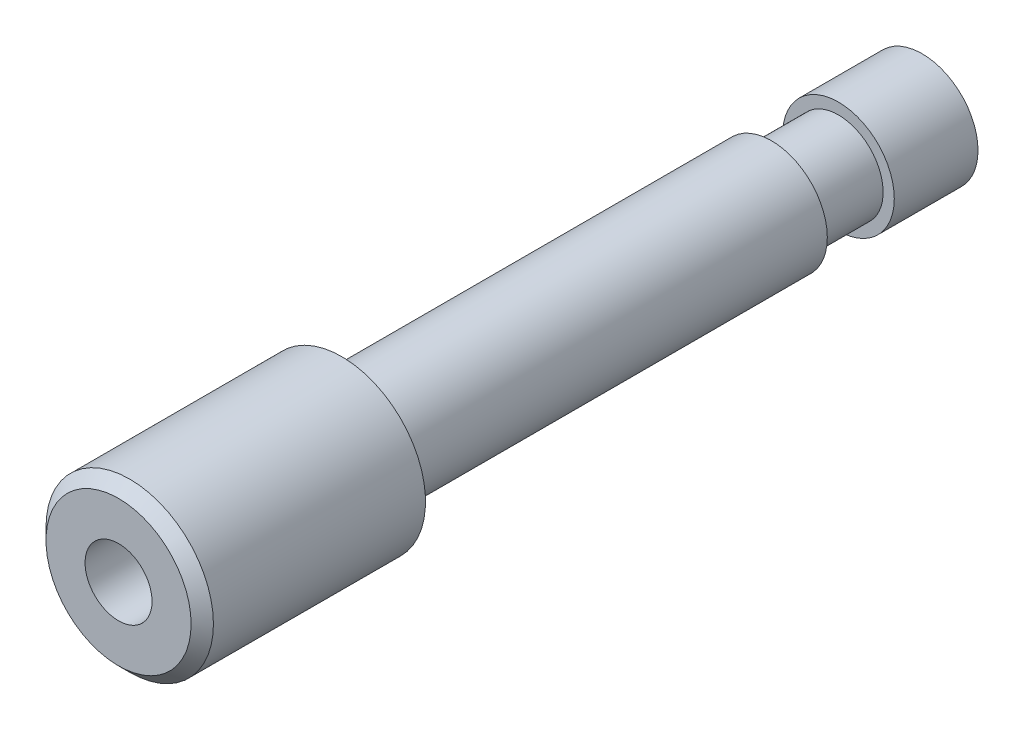
SolidWorks part; units mm, degrees
material "ABS"
ref_plane "Plan de face" through (0, 0, 0) normal (0, 0, 1) x (1, 0, 0)
ref_plane "Plan de dessus" through (0, 0, 0) normal (0, 1, 0) x (1, 0, 0)
ref_plane "Plan de droite" through (0, 0, 0) normal (1, 0, 0) x (0, 0, -1)
sketch "Esquisse1" plane through (0, 0, 0) normal (0, 0, 1) x (1, 0, 0)
  circle A0 centre (0, 0) radius 3.75
extrude "Extrusion1" add sketch "Esquisse1" along normal blind 25.5
sketch "Esquisse2" plane through (0, 0, 0) normal (0, 0, -1) x (-1, 0, 0)
  circle A0 centre (0, 0) radius 2.5
extrude "Extrusion2" add sketch "Esquisse2" along normal blind 10.5
sketch "Esquisse3" plane through (0, 0, 25.5) normal (0, 0, 1) x (1, 0, 0)
  circle A0 centre (0, 0) radius 1.5
extrude "Enlèv. mat.-Extru.1" cut sketch "Esquisse3" against normal blind 8
cosmetic thread "Représentation de filetage1" parameters "D1"=8, "D2"=4
sketch "Esquisse5" plane through (0, 0, 0) normal (0, 1, 0) x (1, 0, 0)
  line L0 (2.5, 5.25) -> (7.7862, 5.25) construction
  line L1 (2.5, 0) -> (2.5, 10.5) construction
  line L2 (2, 6.75) -> (5.0978, 6.75)
  line L3 (2, 6.75) -> (2, 3.75)
  line L4 (2, 3.75) -> (5.0978, 3.75)
  line L5 (5.0978, 6.75) -> (5.0978, 3.75)
  dimension "D1" = 0.5
  dimension "D2" = 1.5
  dimension "D3" = 1.5
revolve "Enlèvement de matière-Révolution1" cut sketch "Esquisse5" angle 360 about axis through (0, 0, -10.5) along (0, 0, 1)
sketch "Esquisse6" plane through (0, 0, -10.5) normal (0, 0, -1) x (-1, 0, 0)
  line L0 (-1.1732, 0) -> (1.3034, 0) construction
  line L5 (2.6047, -2.9862) -> (2.6047, -2)
  line L6 (-2.5415, -2) -> (2.6047, -2)
  line L7 (-2.5415, -2.9862) -> (-2.5415, -2)
  line L8 (-2.5415, -2.9862) -> (2.6047, -2.9862)
extrude "Enlèv. mat.-Extru.3" cut sketch "Esquisse6" against normal blind 2
sketch "Esquisse8" plane through (0, 0, 0) normal (0, 0, -1) x (-1, 0, 0)
  circle A0 centre (0, 0) radius 2.5 construction
  circle A1 centre (0, 0) radius 2.5
extrude "Extrusion5" cut sketch "Esquisse8" against normal blind 15.5 flip side to cut
chamfer "Chanfrein1" distance 0.5 angle 45 1 edges at (3.75, 0, 25.5)
